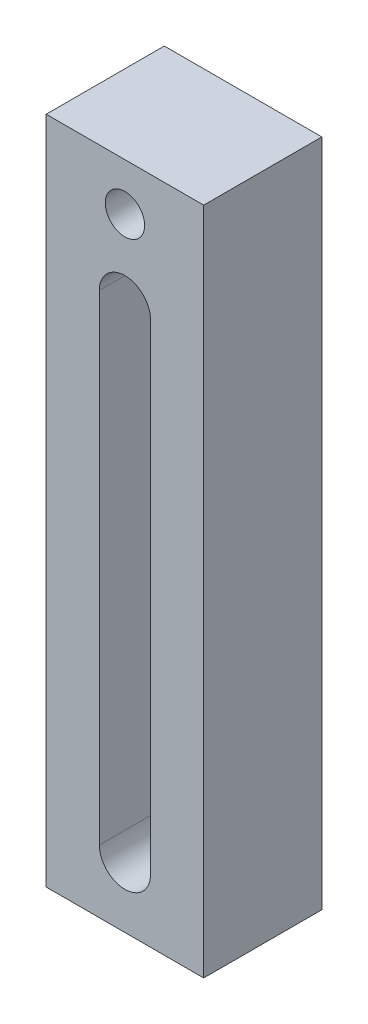
SolidWorks part; units mm, degrees
ref_plane "Plan de face" through (0, 0, 0) normal (0, 0, 1) x (1, 0, 0)
ref_plane "Plan de dessus" through (0, 0, 0) normal (0, 1, 0) x (1, 0, 0)
ref_plane "Plan de droite" through (0, 0, 0) normal (1, 0, 0) x (0, 0, -1)
sketch "Esquisse1" plane through (0, 0, 0) normal (0, 0, 1) x (1, 0, 0)
  line L1 (0, 0) -> (20, 0)
  line L2 (0, 0) -> (0, 85)
  line L3 (0, 85) -> (20, 85)
  line L4 (20, 0) -> (20, 85)
  dimension "D1" = 20
  dimension "D2" = 85
extrude "Boss.-Extru.1" add sketch "Esquisse1" along normal blind 15
sketch "Esquisse2" plane through (0, 0, 15) normal (0, 0, 1) x (1, 0, 0)
  line L0 (10, 0) -> (10, 85) construction
  line L1 (0, 0) -> (20, 0) construction
  line L2 (20, 85) -> (0, 85) construction
  line L3 (10, 8) -> (10, 69) construction
  line L4 (6.75, 8) -> (6.75, 69)
  line L5 (13.25, 8) -> (13.25, 69)
  arc A0 (6.75, 8) -> (13.25, 8) centre (10, 8) ccw
  arc A1 (13.25, 69) -> (6.75, 69) centre (10, 69) ccw
  circle A2 centre (10, 79) radius 2.5
  point P8 (10, 38.5)
  dimension "D4" = 5
  dimension "D1" = 6.5
  dimension "D2" = 61
  dimension "D3" = 8
  dimension "D5" = 6
extrude "Enlèv. mat.-Extru.1" cut sketch "Esquisse2" against normal up to vertex (15 mm away) up to point (20, 85, 0)
